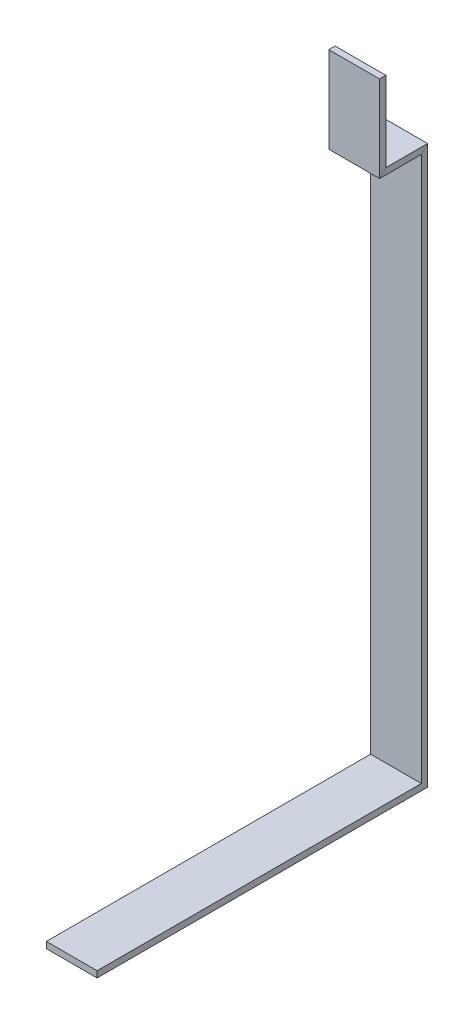
SolidWorks part; units mm, degrees
ref_plane "Alzado" through (0, 0, 0) normal (0, 0, 1) x (1, 0, 0)
ref_plane "Planta" through (0, 0, 0) normal (0, 1, 0) x (1, 0, 0)
ref_plane "Vista lateral" through (0, 0, 0) normal (1, 0, 0) x (0, 0, -1)
sketch "Croquis1" plane through (0, 0, 0) normal (0, 0, 1) x (1, 0, 0)
  line L1 (-25.4, 3.155) -> (25.4, 3.155)
  line L2 (-25.4, 3.155) -> (-25.4, -3.155)
  line L3 (-25.4, -3.155) -> (25.4, -3.155)
  line L4 (25.4, 3.155) -> (25.4, -3.155)
  line L5 (-25.4, 3.155) -> (25.4, -3.155) construction
  line L6 (-25.4, -3.155) -> (25.4, 3.155) construction
  point P0 (0, 0)
  dimension "D1" = 50.8
  dimension "D2" = 6.31
extrude "Saliente-Extruir1" add sketch "Croquis1" along normal blind 330.7
sketch "Croquis3" plane through (0, -3.155, 0) normal (0, -1, 0) x (1, 0, 0)
  line L0 (-25.4, 330.7) -> (-25.4, 0) construction
  line L1 (25.4, 0) -> (-25.4, 0)
  line L2 (25.4, 0) -> (25.4, 6.31)
  line L3 (25.4, 6.31) -> (-25.4, 6.31)
  line L4 (-25.4, 0) -> (-25.4, 6.31)
  line L5 (25.4, 0) -> (-25.4, 6.31) construction
  line L6 (25.4, 6.31) -> (-25.4, 0) construction
  line L7 (25.4, 330.7) -> (25.4, 0) construction
  line L8 (-25.4, 0) -> (25.4, 0) construction
  point P0 (0, 3.155)
  dimension "D1" = 6.31
extrude "Saliente-Extruir2" add sketch "Croquis3" against normal blind 544.51
sketch "Croquis4" plane through (0, 541.355, 0) normal (0, 1, 0) x (1, 0, 0)
  line L0 (25.4, -6.31) -> (-25.4, -6.31)
  line L1 (-25.4, -6.31) -> (-25.4, 0)
  line L2 (-25.4, 0) -> (25.4, 0)
  line L3 (25.4, 0) -> (25.4, -6.31)
  line L4 (0, 0) -> (0, -6.31) construction
  line L5 (0, -6.31) -> (0, -3.155) construction
  line L6 (0, -3.155) -> (-25.4, -3.155) construction
sketch3d "Croquis3D1"
  line L0 (0, 541.355, 3.155) -> (0, 551.355, 3.155)
  line L2 (0, 551.355, 3.155) -> (0, 551.355, 44.965)
  line L3 (0, 551.355, 44.965) -> (0, 634.515, 44.965)
  dimension "D1" = 10
  dimension "D2" = 41.81
  dimension "D3" = 83.16
sweep "Barrer1" add profiles "Croquis4" path "Croquis3D1"
